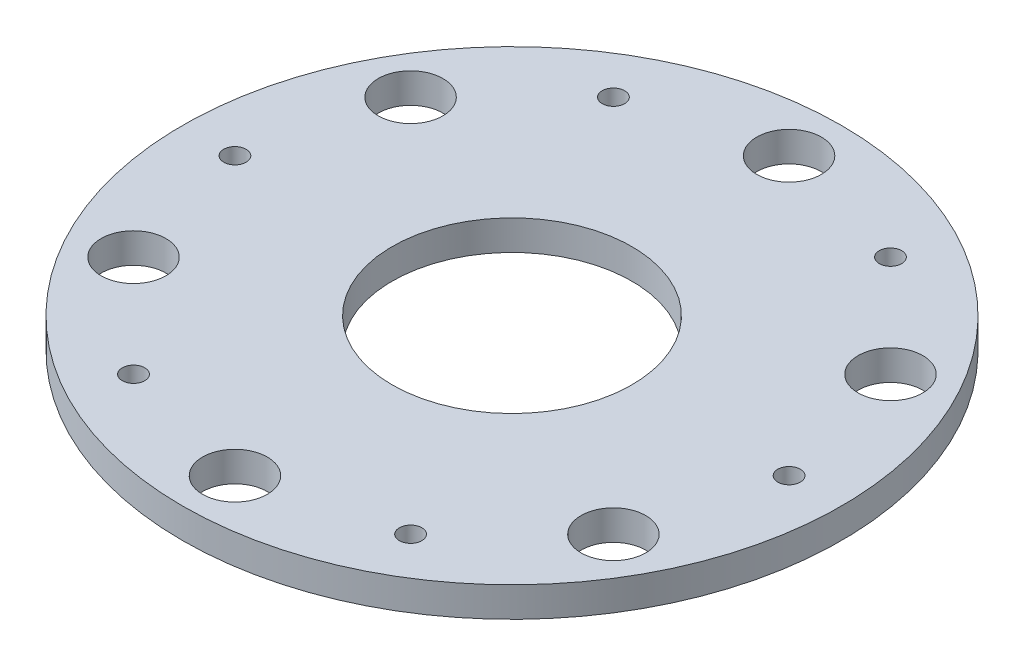
SolidWorks part; units mm, degrees
ref_plane "Front Plane" through (0, 0, 0) normal (0, 0, 1) x (1, 0, 0)
ref_plane "Top Plane" through (0, 0, 0) normal (0, 1, 0) x (1, 0, 0)
ref_plane "Right Plane" through (0, 0, 0) normal (1, 0, 0) x (0, 0, -1)
sketch "Sketch1" plane through (0, 0, 0) normal (0, 1, 0) x (1, 0, 0)
  line L0 (0, 0) -> (0, 29.3624) construction
  line L1 (0, 0) -> (-14.6812, 25.4286) construction
  circle A0 centre (0, 0) radius 34.925
  circle A1 centre (0, 0) radius 12.7
  circle A2 centre (0, 29.3624) radius 3.429
  circle A3 centre (25.4286, 14.6812) radius 3.429
  circle A4 centre (25.4286, -14.6812) radius 3.429
  circle A5 centre (0, -29.3624) radius 3.429
  circle A6 centre (-25.4286, -14.6812) radius 3.429
  circle A7 centre (-25.4286, 14.6812) radius 3.429
  circle A8 centre (0, 0) radius 29.3624
  dimension "D1" = 69.85
  dimension "D2" = 25.4
  dimension "D3" = 6.858
  dimension "D4" = 29.3624
  dimension "D6" = 30
  dimension "D5" = 6
extrude "Boss-Extrude1" add sketch "Sketch1" along normal blind 3.175
hole_wizard "Tap Drill for #2 Helicoil1" positions "Sketch4" profile "Sketch5" hole size "#2-56" standard "ANSI Inch" end condition through all
sketch "Sketch4" plane through (0, 0, 0) normal (0, -1, 0) x (-1, 0, 0)
  point P0 (14.6812, 25.4286)
sketch "Sketch5" plane through (-14.6812, 0, -25.4286) normal (1, 0, 0) x (0, 0, -1)
  line L0 (0, 0) -> (0, 3.175)
  line L1 (0, 3.175) -> (1.1913, 3.175)
  line L2 (1.1913, 3.175) -> (1.1913, 0)
  line L5 (1.1913, 0) -> (0, 0)
  line L11 (0, -6.35) -> (0, 107.95) construction
  dimension "Thru Hole Dia." = 2.3825
  dimension "Thru Hole Depth" = 3.175
pattern_circular "CirPattern1" count 6 over 360 about axis through (0, 0, 0) along (0, 1, 0) of "Tap Drill for #2 Helicoil1"
